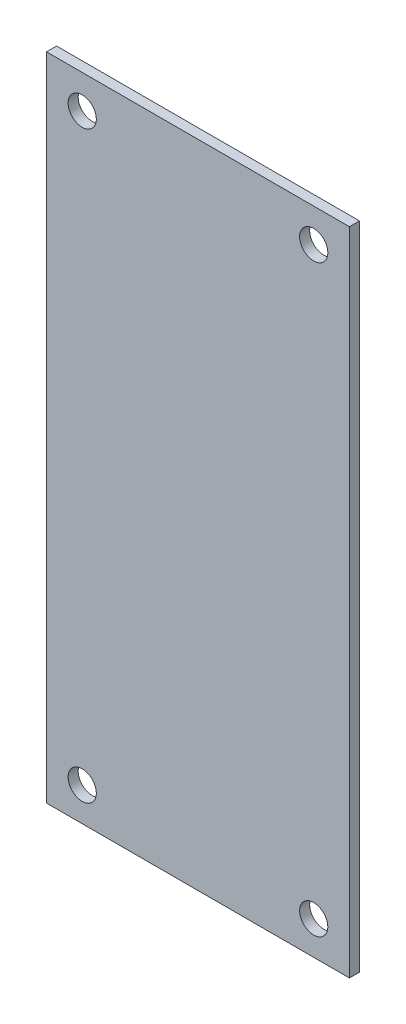
SolidWorks part; units mm, degrees
ref_plane "Alzado" through (0, 0, 0) normal (0, 0, 1) x (1, 0, 0)
ref_plane "Planta" through (0, 0, 0) normal (0, 1, 0) x (1, 0, 0)
ref_plane "Vista lateral" through (0, 0, 0) normal (1, 0, 0) x (0, 0, -1)
sketch "Croquis1" plane through (0, 0, 0) normal (0, 0, 1) x (1, 0, 0)
  line L0 (-11.5, -29) -> (11.5, -29) construction
  line L1 (15.05, -32.3215) -> (-15.05, -32.3215)
  line L2 (15.05, -32.3215) -> (15.05, 32.3215)
  line L3 (15.05, 32.3215) -> (-15.05, 32.3215)
  line L4 (-15.05, -32.3215) -> (-15.05, 32.3215)
  line L5 (15.05, -32.3215) -> (-15.05, 32.3215) construction
  line L6 (15.05, 32.3215) -> (-15.05, -32.3215) construction
  line L7 (-15.05, 0) -> (15.05, 0) construction
  circle A0 centre (-11.5, -29) radius 1.4
  circle A1 centre (11.5, -29) radius 1.4
  circle A2 centre (11.5, 29) radius 1.4
  circle A3 centre (-11.5, 29) radius 1.4
  point P0 (0, 0)
  point P10 (0, -29)
  dimension "D3" = 2.8
  dimension "D4" = 23
  dimension "D5" = 29
  dimension "D1" = 64.643
  dimension "D2" = 30.1
extrude "Saliente-Extruir1" add sketch "Croquis1" along normal blind 1
